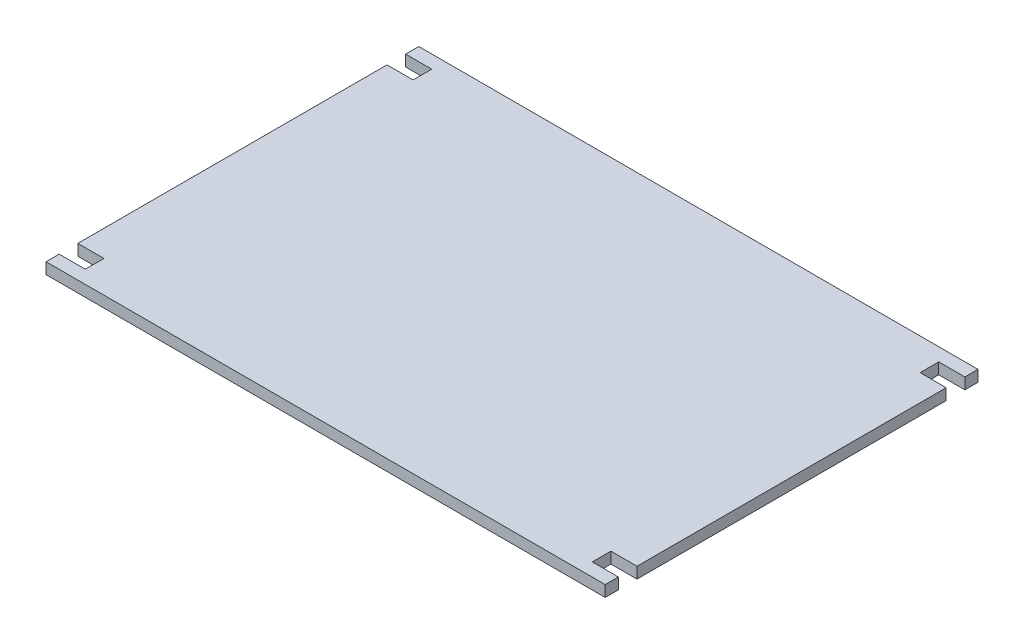
SolidWorks part; units mm, degrees
ref_plane "Front Plane" through (0, 0, 0) normal (0, 0, 1) x (1, 0, 0)
ref_plane "Top Plane" through (0, 0, 0) normal (0, 1, 0) x (1, 0, 0)
ref_plane "Right Plane" through (0, 0, 0) normal (1, 0, 0) x (0, 0, -1)
sketch "Sketch1" plane through (0, 0, 0) normal (0, 1, 0) x (1, 0, 0)
  line L1 (0, 0) -> (150, 0)
  line L2 (0, 0) -> (0, -100)
  line L3 (0, -100) -> (150, -100)
  line L4 (150, 0) -> (150, -100)
  dimension "D1" = 150
  dimension "D2" = 100
extrude "Boss-Extrude1" add sketch "Sketch1" along normal blind 3
sketch "Sketch2" plane through (0, 3, 0) normal (0, 1, 0) x (1, 0, 0)
  line L0 (150, -96.4665) -> (143, -96.4665)
  line L1 (150, -100) -> (150, 0) construction
  line L2 (143, -96.4665) -> (143, -91.4665)
  line L3 (143, -91.4665) -> (150, -91.4665)
  line L4 (150, -91.4665) -> (150, -96.4665)
  line L5 (150, -50) -> (0, -50) construction
  line L6 (0, 0) -> (0, -100) construction
  line L7 (143, -3.5335) -> (143, -8.5335)
  line L8 (150, -3.5335) -> (143, -3.5335)
  line L9 (150, -8.5335) -> (150, -3.5335)
  line L10 (143, -8.5335) -> (150, -8.5335)
  line L11 (75, 0) -> (75, -100) construction
  line L12 (150, 0) -> (0, 0) construction
  line L13 (0, -100) -> (150, -100) construction
  line L14 (0, -91.4665) -> (0, -96.4665)
  line L15 (0, -8.5335) -> (0, -3.5335)
  line L16 (0, -3.5335) -> (7, -3.5335)
  line L17 (7, -3.5335) -> (7, -8.5335)
  line L18 (7, -8.5335) -> (0, -8.5335)
  line L19 (7, -91.4665) -> (0, -91.4665)
  line L20 (7, -96.4665) -> (7, -91.4665)
  line L21 (0, -96.4665) -> (7, -96.4665)
  dimension "D1" = 7
  dimension "D2" = 5
extrude "Cut-Extrude1" cut sketch "Sketch2" against normal blind 3
